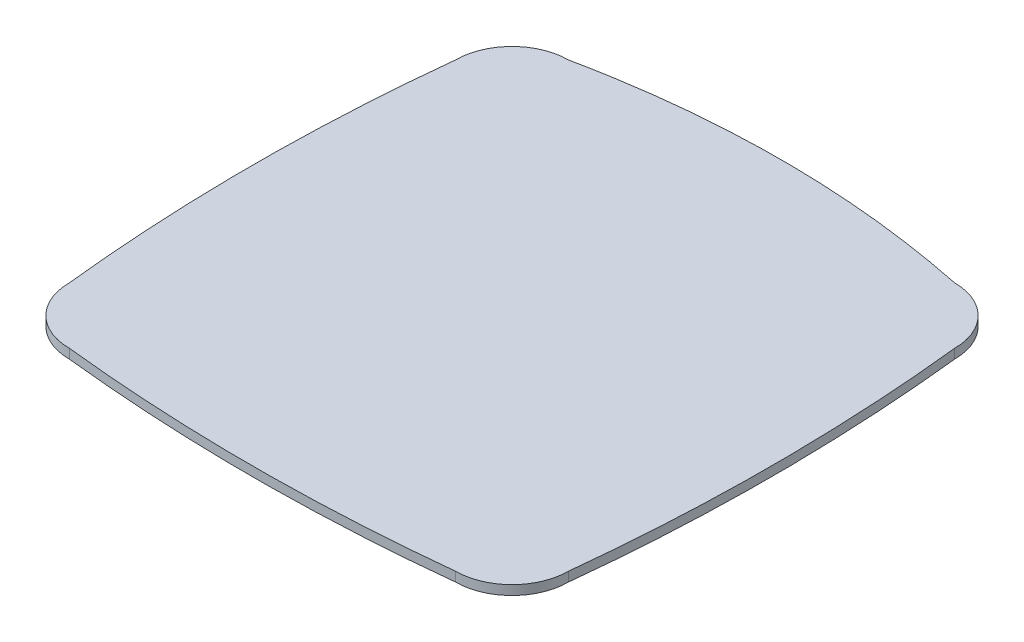
SolidWorks part; units mm, degrees
ref_plane "Front Plane" through (0, 0, 0) normal (0, 0, 1) x (1, 0, 0)
ref_plane "Top Plane" through (0, 0, 0) normal (0, 1, 0) x (1, 0, 0)
ref_plane "Right Plane" through (0, 0, 0) normal (1, 0, 0) x (0, 0, -1)
sketch "Sketch1" plane through (0, 0, 0) normal (0, 1, 0) x (1, 0, 0)
  arc A0 (26.035, 33.655) -> (33.655, 26.035) centre (26.035, 26.035) cw
  arc A1 (33.655, -26.035) -> (26.035, -33.655) centre (26.035, -26.035) cw
  arc A2 (-26.035, -33.655) -> (-33.655, -26.035) centre (-26.035, -26.035) cw
  arc A3 (-26.035, 33.655) -> (-33.655, 26.035) centre (-26.035, 26.035) ccw
  spline S0 degree 2 poles (-33.655, 26.035) (-36.449, 0) (-33.655, -26.035) knots 0 0 0 1 1 1
  spline S1 degree 2 poles (-26.035, 33.655) (0, 39.0371) (26.035, 33.655) knots 0 0 0 1 1 1
  spline S2 degree 2 poles (33.655, 26.035) (36.449, 0) (33.655, -26.035) knots 0 0 0 1 1 1
  spline S3 degree 2 poles (-26.035, -33.655) (0, -36.449) (26.035, -33.655) knots 0 0 0 1 1 1
  point P0 (0, 0)
  point P11 (0, 0)
  dimension "D1" = 7.62
extrude "Boss-Extrude1" add sketch "Sketch1" along normal blind 1.27
